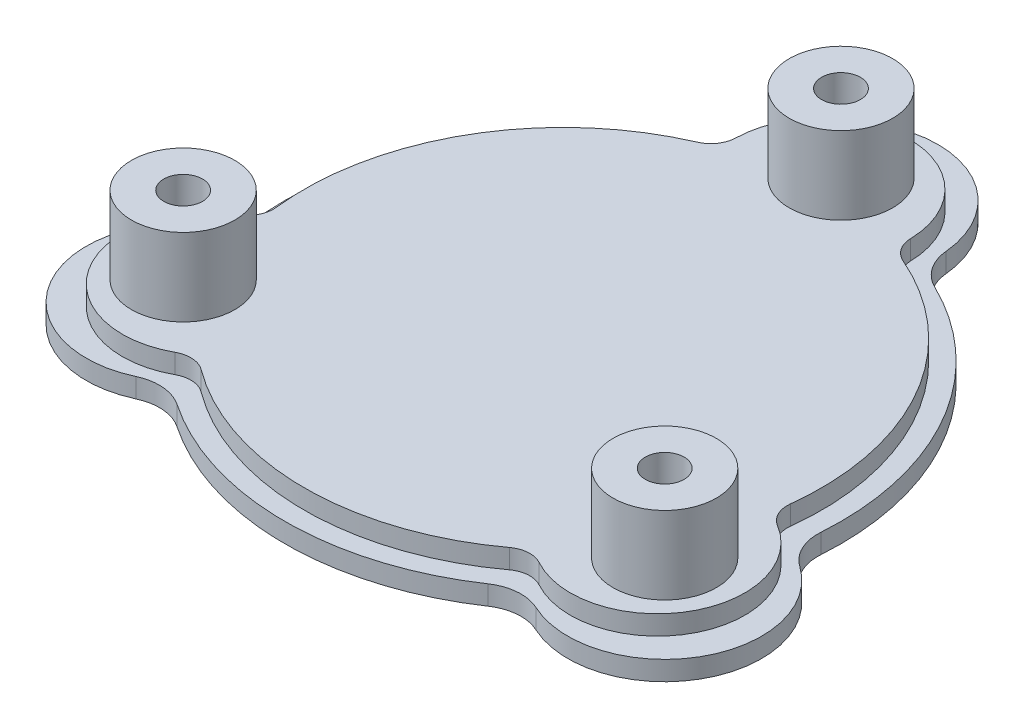
SolidWorks part; units mm, degrees
ref_plane "Front Plane" through (0, 0, 0) normal (0, 0, 1) x (1, 0, 0)
ref_plane "Top Plane" through (0, 0, 0) normal (0, 1, 0) x (1, 0, 0)
ref_plane "Right Plane" through (0, 0, 0) normal (1, 0, 0) x (0, 0, -1)
sketch "Sketch1" plane through (0, 0, 0) normal (0, 1, 0) x (1, 0, 0)
  line L0 (0, -55) -> (0, 55) construction
  circle A0 centre (0, 43) radius 3
  circle A1 centre (0, 43) radius 6
  arc A2 (14.9415, 44.324) -> (-14.9415, 44.324) centre (0, 43) ccw
  arc A3 (-18.8462, 38.65) -> (-42.895, -3.0038) centre (0, 0) ccw
  arc A4 (-18.8462, 38.65) -> (-14.9415, 44.324) centre (-21.9141, 44.9419) ccw
  arc A6 (18.8462, 38.65) -> (14.9415, 44.324) centre (21.9141, 44.9419) cw
  arc A7 (30.915, -35.1017) -> (45.8564, -9.2223) centre (37.2391, -21.5) ccw
  arc A8 (42.895, -3.0038) -> (45.8564, -9.2223) centre (49.8779, -3.4927) ccw
  arc A9 (24.0488, -35.6462) -> (30.915, -35.1017) centre (27.9637, -41.4491) cw
  arc A10 (-45.8564, -9.2223) -> (-30.915, -35.1017) centre (-37.2391, -21.5) ccw
  arc A11 (-24.0488, -35.6462) -> (-30.915, -35.1017) centre (-27.9637, -41.4491) ccw
  arc A12 (-42.895, -3.0038) -> (-45.8564, -9.2223) centre (-49.8779, -3.4927) cw
  arc A13 (-24.0488, -35.6462) -> (24.0488, -35.6462) centre (0, 0) ccw
  arc A14 (42.895, -3.0038) -> (18.8462, 38.65) centre (0, 0) ccw
  circle A15 centre (-37.2391, -21.5) radius 6
  circle A16 centre (-37.2391, -21.5) radius 3
  circle A17 centre (37.2391, -21.5) radius 6
  circle A18 centre (37.2391, -21.5) radius 3
  point P32 (0, 0)
  dimension "D1" = 12
  dimension "D2" = 30
  dimension "D4" = 14
  dimension "D6" = 6
  dimension "D7" = 12
  dimension "D8" = 6
  dimension "D9" = 12
  dimension "D10" = 6
  dimension "D3" = 43
  dimension "D5" = 3
extrude "Boss-Extrude1" add sketch "Sketch1" along normal blind 3 contours A8 A14 A6 A2 A4 A3 A12 A10 A11 A13 A9 A7 A17 A15 A1 | A15 A16 | A17 A18 | A1 A0
sketch "Sketch3" plane through (0, 3, 0) normal (0, 1, 0) x (1, 0, 0)
  line L0 (0, -1.65) -> (0, 1.65) construction
  circle A0 centre (0, 43) radius 3
  arc A1 (13.497, 40.2869) -> (-13.497, 40.2869) centre (0, 40) ccw
  arc A2 (-15.9055, 36.7017) -> (-39.7374, -4.5763) centre (0, 0) ccw
  arc A3 (-15.9055, 36.7017) -> (-13.497, 40.2869) centre (-17.496, 40.3719) ccw
  arc A4 (15.9055, 36.7017) -> (13.497, 40.2869) centre (17.496, 40.3719) cw
  circle A5 centre (-37.2391, -21.5) radius 3
  arc A6 (28.141, -31.8321) -> (41.6379, -8.4547) centre (34.641, -20) ccw
  arc A7 (39.7374, -4.5763) -> (41.6379, -8.4547) centre (43.7111, -5.0339) ccw
  arc A8 (23.8319, -32.1254) -> (28.141, -31.8321) centre (26.215, -35.338) cw
  arc A9 (-41.6379, -8.4547) -> (-28.141, -31.8321) centre (-34.641, -20) ccw
  arc A10 (-23.8319, -32.1254) -> (-28.141, -31.8321) centre (-26.215, -35.338) ccw
  arc A11 (-39.7374, -4.5763) -> (-41.6379, -8.4547) centre (-43.7111, -5.0339) cw
  arc A12 (-23.8319, -32.1254) -> (23.8319, -32.1254) centre (0, 0) ccw
  arc A13 (39.7374, -4.5763) -> (15.9055, 36.7017) centre (0, 0) ccw
  circle A14 centre (37.2391, -21.5) radius 3
  point P33 (0, 0)
  dimension "D2" = 27
  dimension "D3" = 80
  dimension "D4" = 8
  dimension "D1" = 3
  dimension "D5" = 3
extrude "Boss-Extrude3" add sketch "Sketch3" along normal blind 3
sketch "Sketch4" plane through (0, 6, 0) normal (0, 1, 0) x (1, 0, 0)
  circle A0 centre (0, 43) radius 8
  circle A1 centre (0, 43) radius 3
  dimension "D1" = 16
extrude "Boss-Extrude4" add sketch "Sketch4" along normal blind 12
sketch "Sketch6" plane through (0, 6, 0) normal (0, 1, 0) x (1, 0, 0)
  circle A0 centre (-37.2391, -21.5) radius 8
  circle A1 centre (-37.2391, -21.5) radius 3
  circle A2 centre (37.2391, -21.5) radius 8
  circle A3 centre (37.2391, -21.5) radius 3
  dimension "D1" = 16
  dimension "D2" = 16
extrude "Boss-Extrude5" add sketch "Sketch6" along normal blind 12
